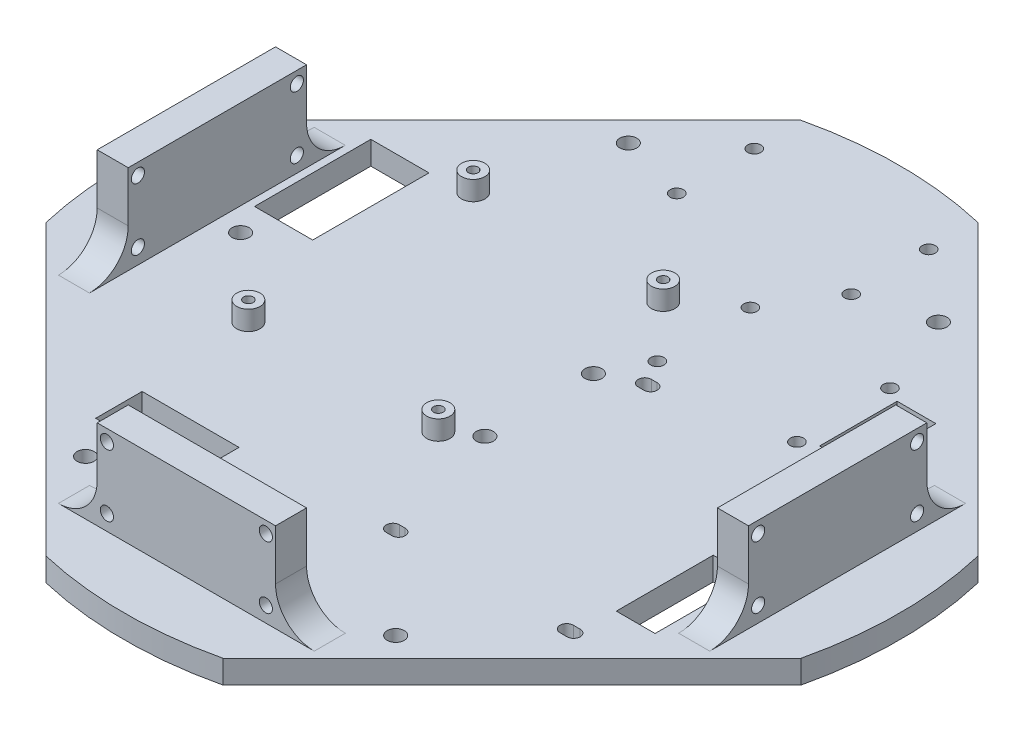
SolidWorks part; units mm, degrees
ref_plane "Front Plane" through (0, 0, 0) normal (0, 0, 1) x (1, 0, 0)
ref_plane "Top Plane" through (0, 0, 0) normal (0, 1, 0) x (1, 0, 0)
ref_plane "Right Plane" through (0, 0, 0) normal (1, 0, 0) x (0, 0, -1)
sketch "Sketch1" plane through (0, 0, 0) normal (0, 1, 0) x (1, 0, 0)
  line L2 (97.3532, -22.8549) -> (22.8549, -97.3532)
  line L3 (97.3532, 22.8549) -> (22.8549, 97.3532)
  line L4 (-22.8549, 97.3532) -> (-97.3532, 22.8549)
  line L5 (-22.8549, -97.3532) -> (-97.3532, -22.8549)
  line L6 (100, 0) -> (-100, 0) construction
  line L7 (0, 100) -> (0, -100) construction
  arc A0 (-22.8549, -97.3532) -> (22.8549, -97.3532) centre (0, 0) ccw
  arc A1 (97.3532, -22.8549) -> (97.3532, 22.8549) centre (0, 0) ccw
  arc A2 (22.8549, 97.3532) -> (-22.8549, 97.3532) centre (0, 0) ccw
  arc A4 (-97.3532, 22.8549) -> (-97.3532, -22.8549) centre (0, 0) ccw
  dimension "D2" = 200
  dimension "D1" = 170
  dimension "D3" = 170
extrude "Boss-Extrude1" add sketch "Sketch1" along normal blind 6
sketch "Sketch2" plane through (0, 6, 0) normal (0, 1, 0) x (1, 0, 0)
  line L0 (3.5, -14) -> (10.5, -14) construction
  line L1 (-52.5, 42.5) -> (3.5, 42.5) construction
  line L2 (-52.5, 42.5) -> (-52.5, -42.5) construction
  line L3 (-52.5, -42.5) -> (3.5, -42.5) construction
  line L4 (3.5, 42.5) -> (3.5, -42.5) construction
  line L5 (-52.5, 42.5) -> (3.5, -42.5) construction
  line L6 (-52.5, -42.5) -> (3.5, 42.5) construction
  line L7 (10.5, 21) -> (60.5, 21) construction
  line L8 (10.5, 21) -> (10.5, -49) construction
  line L9 (10.5, -49) -> (60.5, -49) construction
  line L10 (60.5, 21) -> (60.5, -49) construction
  line L11 (10.5, 21) -> (60.5, -49) construction
  line L12 (10.5, -49) -> (60.5, 21) construction
  line L13 (10.5, 51) -> (50.5, 51) construction
  line L14 (10.5, 51) -> (10.5, 23) construction
  line L15 (10.5, 23) -> (50.5, 23) construction
  line L16 (50.5, 51) -> (50.5, 23) construction
  line L17 (10.5, 51) -> (50.5, 23) construction
  line L18 (10.5, 23) -> (50.5, 51) construction
  line L19 (-24.5, 0) -> (24.5, 0) construction
  line L20 (15.75, 18.5) -> (17.25, 18.5) construction
  line L21 (12.5, 25) -> (48.5, 25) construction
  line L22 (12.5, 25) -> (12.5, 49) construction
  line L23 (12.5, 49) -> (48.5, 49) construction
  line L24 (48.5, 25) -> (48.5, 49) construction
  line L25 (12.5, 25) -> (48.5, 49) construction
  line L26 (12.5, 49) -> (48.5, 25) construction
  line L27 (16.5, -46.5) -> (61.5, -46.5) construction
  line L28 (16.5, -46.5) -> (16.5, 18.5) construction
  line L29 (16.5, 18.5) -> (61.5, 18.5) construction
  line L30 (61.5, -46.5) -> (61.5, 18.5) construction
  line L33 (15.75, 20.2) -> (17.25, 20.2)
  line L34 (15.75, 16.8) -> (17.25, 16.8)
  line L35 (60.6, 18.5) -> (62.4, 18.5) construction
  line L36 (60.6, 20.2) -> (62.4, 20.2)
  line L37 (60.6, 16.8) -> (62.4, 16.8)
  line L38 (15.75, -46.5) -> (17.25, -46.5) construction
  line L39 (15.75, -44.8) -> (17.25, -44.8)
  line L40 (15.75, -48.2) -> (17.25, -48.2)
  line L41 (60.6, -46.5) -> (62.4, -46.5) construction
  line L42 (60.6, -44.8) -> (62.4, -44.8)
  line L43 (60.6, -48.2) -> (62.4, -48.2)
  line L44 (-70, 0) -> (70, 0) construction
  line L45 (-49, -19) -> (0, -19) construction
  line L46 (-49, -19) -> (-49, 39) construction
  line L47 (-49, 39) -> (0, 39) construction
  line L48 (0, -19) -> (0, 39) construction
  line L49 (-49, -19) -> (0, 39) construction
  line L50 (-49, 39) -> (0, -19) construction
  line L51 (-25, 87.5) -> (25, 87.5) construction
  line L52 (-25, 87.5) -> (-25, 62.5) construction
  line L53 (-25, 62.5) -> (25, 62.5) construction
  line L54 (25, 87.5) -> (25, 62.5) construction
  line L55 (-25, 87.5) -> (25, 62.5) construction
  line L56 (-25, 62.5) -> (25, 87.5) construction
  line L57 (-22.5, 65) -> (22.5, 65) construction
  line L58 (-22.5, 65) -> (-22.5, 85) construction
  line L59 (-22.5, 85) -> (22.5, 85) construction
  line L60 (22.5, 65) -> (22.5, 85) construction
  line L61 (-22.5, 65) -> (22.5, 85) construction
  line L62 (-22.5, 85) -> (22.5, 65) construction
  line L63 (-40, -70) -> (40, -70) construction
  line L64 (-40, -70) -> (-40, 70) construction
  line L65 (-40, 70) -> (40, 70) construction
  line L66 (40, -70) -> (40, 70) construction
  line L67 (-40, -70) -> (40, 70) construction
  line L68 (-40, 70) -> (40, -70) construction
  line L69 (3.5, 37) -> (10.5, 37) construction
  line L73 (-7.9, -10.25) -> (7.9, -10.25) construction
  line L74 (-7.9, -10.25) -> (-7.9, 10.25) construction
  line L75 (-7.9, 10.25) -> (7.9, 10.25) construction
  line L76 (7.9, -10.25) -> (7.9, 10.25) construction
  line L77 (-7.9, -10.25) -> (7.9, 10.25) construction
  line L78 (-7.9, 10.25) -> (7.9, -10.25) construction
  line L79 (7, -14) -> (7, 15.9726) construction
  line L80 (-7.4775, -48.1913) -> (-7.4775, -60.1913) construction
  line L81 (-19.4775, -46.1913) -> (-5.4775, -46.1913) construction
  line L82 (-19.4775, -46.1913) -> (-19.4775, -62.1913) construction
  line L83 (-19.4775, -62.1913) -> (-5.4775, -62.1913) construction
  line L84 (-5.4775, -46.1913) -> (-5.4775, -62.1913) construction
  line L85 (-19.4775, -46.1913) -> (-5.4775, -62.1913) construction
  line L86 (-19.4775, -62.1913) -> (-5.4775, -46.1913) construction
  line L87 (-31.848, 63.9028) -> (-31.848, 51.9028) construction
  line L88 (-43.848, 65.9028) -> (-29.848, 65.9028) construction
  line L89 (-43.848, 65.9028) -> (-43.848, 49.9028) construction
  line L90 (-43.848, 49.9028) -> (-29.848, 49.9028) construction
  line L91 (-29.848, 65.9028) -> (-29.848, 49.9028) construction
  line L92 (-43.848, 65.9028) -> (-29.848, 49.9028) construction
  line L93 (-43.848, 49.9028) -> (-29.848, 65.9028) construction
  line L95 (-47.2186, -48.1913) -> (-22.2186, -48.1913)
  line L96 (-47.2186, -48.1913) -> (-47.2186, -60.1913)
  line L97 (-47.2186, -60.1913) -> (-22.2186, -60.1913)
  line L98 (-22.2186, -48.1913) -> (-22.2186, -60.1913)
  line L99 (-47.2186, -48.1913) -> (-22.2186, -60.1913) construction
  line L100 (-47.2186, -60.1913) -> (-22.2186, -48.1913) construction
  line L101 (52.3441, 47) -> (62.3441, 47)
  line L102 (52.3441, 47) -> (52.3441, 27)
  line L103 (52.3441, 27) -> (62.3441, 27)
  line L104 (62.3441, 47) -> (62.3441, 27)
  line L105 (52.3441, 47) -> (62.3441, 27) construction
  line L106 (52.3441, 27) -> (62.3441, 47) construction
  line L107 (-59.0464, 37.6307) -> (-74.0464, 37.6307)
  line L108 (-59.0464, 37.6307) -> (-59.0464, 7.6307)
  line L109 (-59.0464, 7.6307) -> (-74.0464, 7.6307)
  line L110 (-74.0464, 37.6307) -> (-74.0464, 7.6307)
  line L111 (-59.0464, 37.6307) -> (-74.0464, 7.6307) construction
  line L112 (-59.0464, 7.6307) -> (-74.0464, 37.6307) construction
  line L113 (63.0144, -36.1093) -> (73.0144, -36.1093)
  line L114 (63.0144, -36.1093) -> (63.0144, -11.1093)
  line L115 (63.0144, -11.1093) -> (73.0144, -11.1093)
  line L116 (73.0144, -36.1093) -> (73.0144, -11.1093)
  line L117 (63.0144, -36.1093) -> (73.0144, -11.1093) construction
  line L118 (63.0144, -11.1093) -> (73.0144, -36.1093) construction
  circle A0 centre (12.5, 25) radius 1.7
  circle A1 centre (48.5, 25) radius 1.7
  circle A2 centre (48.5, 49) radius 1.7
  circle A3 centre (12.5, 49) radius 1.7
  arc A8 (15.75, 20.2) -> (15.75, 16.8) centre (15.75, 18.5) ccw
  arc A9 (17.25, 16.8) -> (17.25, 20.2) centre (17.25, 18.5) ccw
  arc A10 (60.6, 20.2) -> (60.6, 16.8) centre (60.6, 18.5) ccw
  arc A11 (62.4, 16.8) -> (62.4, 20.2) centre (62.4, 18.5) ccw
  arc A12 (15.75, -44.8) -> (15.75, -48.2) centre (15.75, -46.5) ccw
  arc A13 (17.25, -48.2) -> (17.25, -44.8) centre (17.25, -46.5) ccw
  arc A14 (60.6, -44.8) -> (60.6, -48.2) centre (60.6, -46.5) ccw
  arc A15 (62.4, -48.2) -> (62.4, -44.8) centre (62.4, -46.5) ccw
  circle A16 centre (-49, 39) radius 1.25
  circle A17 centre (0, 39) radius 1.25
  circle A18 centre (-49, -19) radius 1.25
  circle A19 centre (0, -19) radius 1.25
  circle A20 centre (-22.5, 85) radius 1.7
  circle A21 centre (22.5, 85) radius 1.7
  circle A22 centre (22.5, 65) radius 1.7
  circle A23 centre (-22.5, 65) radius 1.7
  circle A24 centre (-40, -70) radius 2.2
  circle A25 centre (40, -70) radius 2.2
  circle A26 centre (40, 70) radius 2.2
  circle A27 centre (-40, 70) radius 2.2
  circle A28 centre (-70, 0) radius 2.2
  circle A29 centre (70, 0) radius 2.2
  circle A30 centre (7, -14) radius 2.2
  circle A31 centre (7, 14) radius 2.2
  point P0 (-24.5, 0)
  point P6 (30.5, 37)
  point P7 (35.5, -14)
  point P22 (30.5, 37)
  point P30 (35.5, -14)
  point P37 (16.5, 18.5)
  point P46 (61.5, 18.5)
  point P51 (16.5, -46.5)
  point P59 (61.5, -46.5)
  point P72 (0, 75)
  point P77 (0, 75)
  point P85 (0, 0)
  point P98 (0, 0)
  point P110 (-12.4775, -54.1913)
  point P118 (-7.4775, -54.1913)
  point P119 (0, 0)
  point P130 (-24.5, 10)
  point P131 (0, 0)
  point P132 (-34.7186, -54.1913)
  point P137 (57.3441, 37)
  point P142 (-66.5464, 22.6307)
  point P148 (57.9835, 36.8207)
  point P149 (68.0144, -23.6093)
  dimension "D8" = 3.4
  dimension "D9" = 3.4
  dimension "D10" = 3.4
  dimension "D11" = 3.4
  dimension "D14" = 1.7
  dimension "D15" = 1.5
  dimension "D16" = 1.7
  dimension "D17" = 1.8
  dimension "D20" = 1.7
  dimension "D21" = 1.7
  dimension "D22" = 1.7
  dimension "D26" = 2.5
  dimension "D27" = 2.5
  dimension "D28" = 2.5
  dimension "D29" = 2.5
  dimension "D33" = 3.4
  dimension "D34" = 3.4
  dimension "D35" = 3.4
  dimension "D36" = 3.4
  dimension "D40" = 4.4
  dimension "D41" = 4.4
  dimension "D42" = 4.4
  dimension "D43" = 4.4
  dimension "D46" = 4.4
  dimension "D47" = 4.4
  dimension "D25" = 4.4
  dimension "D50" = 7
  dimension "D1" = 85
  dimension "D2" = 56
  dimension "D3" = 70
  dimension "D4" = 50
  dimension "D5" = 40
  dimension "D6" = 28
  dimension "D7" = 2
  dimension "D12" = 36
  dimension "D13" = 24
  dimension "D18" = 45
  dimension "D19" = 65
  dimension "D23" = 1.8
  dimension "D24" = 1.5
  dimension "D30" = 25
  dimension "D31" = 50
  dimension "D32" = 75
  dimension "D37" = 20
  dimension "D38" = 45
  dimension "D39" = 80
  dimension "D44" = 140
  dimension "D45" = 140
  dimension "D48" = 15.8
  dimension "D49" = 20.5
  dimension "D51" = 3.5
  dimension "D52" = 28
  dimension "D53" = 16
  dimension "D54" = 14
  dimension "D57" = 12
  dimension "D58" = 2
  dimension "D59" = 16
  dimension "D60" = 14
  dimension "D63" = 12
  dimension "D64" = 2
  dimension "D65" = 58
  dimension "D66" = 49
  dimension "D67" = 3.5
  dimension "D68" = 12
  dimension "D69" = 25
  dimension "D70" = 10
  dimension "D71" = 20
  dimension "D72" = 15
  dimension "D73" = 30
  dimension "D74" = 10
  dimension "D75" = 25
  dimension "D76" = 6
extrude "Cut-Extrude1" cut sketch "Sketch2" against normal through all
sketch "Sketch3" plane through (0, 6, 0) normal (0, 1, 0) x (1, 0, 0)
  line L0 (0, -80) -> (0, 0) construction
  line L1 (-84, -23) -> (-76, -23)
  line L2 (-84, -23) -> (-84, 23)
  line L3 (-84, 23) -> (-76, 23)
  line L4 (-76, -23) -> (-76, 23)
  line L5 (-84, -23) -> (-76, 23) construction
  line L6 (-84, 23) -> (-76, -23) construction
  line L7 (-23, -84) -> (23, -84)
  line L8 (-23, -84) -> (-23, -76)
  line L9 (-23, -76) -> (23, -76)
  line L10 (23, -84) -> (23, -76)
  line L11 (-23, -84) -> (23, -76) construction
  line L12 (-23, -76) -> (23, -84) construction
  line L13 (84, 23) -> (76, -23) construction
  line L14 (84, -23) -> (76, 23) construction
  line L15 (76, -23) -> (76, 23)
  line L16 (84, 23) -> (76, 23)
  line L17 (84, -23) -> (84, 23)
  line L18 (84, -23) -> (76, -23)
  point P0 (-80, 0)
  point P5 (0, -80)
  point P17 (80, 0)
  dimension "D1" = 8
  dimension "D2" = 8
  dimension "D3" = 46
  dimension "D4" = 46
  dimension "D5" = 80
  dimension "D6" = 80
extrude "Boss-Extrude2" add sketch "Sketch3" along normal blind 23
sketch "Sketch4" plane through (-84, 0, 0) normal (-1, 0, 0) x (0, 0, 1)
  line L1 (-20.5, 10) -> (20.5, 10) construction
  line L2 (-20.5, 10) -> (-20.5, 26) construction
  line L3 (-20.5, 26) -> (20.5, 26) construction
  line L4 (20.5, 10) -> (20.5, 26) construction
  line L5 (-20.5, 10) -> (20.5, 26) construction
  line L6 (-20.5, 26) -> (20.5, 10) construction
  line L7 (0, 18) -> (0, 58.729) construction
  line L8 (-22.5, 8) -> (22.5, 8) construction
  line L9 (-23, 29) -> (23, 29) construction
  line L10 (-22.5, 8) -> (-22.5, 28) construction
  line L11 (-22.5, 28) -> (22.5, 28) construction
  line L12 (22.5, 8) -> (22.5, 28) construction
  line L13 (-22.5, 8) -> (22.5, 28) construction
  line L14 (-22.5, 28) -> (22.5, 8) construction
  circle A1 centre (-20.5, 26) radius 1.7
  circle A2 centre (20.5, 26) radius 1.7
  circle A3 centre (20.5, 10) radius 1.7
  circle A4 centre (-20.5, 10) radius 1.7
  point P0 (0, 18)
  dimension "D1" = 3.4
  dimension "D2" = 3.4
  dimension "D3" = 3.4
  dimension "D4" = 3.4
  dimension "D5" = 11
  dimension "D6" = 16
  dimension "D7" = 45
  dimension "D8" = 20
  dimension "D9" = 41
extrude "Cut-Extrude2" cut sketch "Sketch4" against normal through all
sketch "Sketch5" plane through (0, 0, 84) normal (0, 0, 1) x (1, 0, 0)
  line L0 (-20.5, 10) -> (20.5, 10) construction
  line L1 (-20.5, 10) -> (-20.5, 26) construction
  line L2 (-20.5, 26) -> (20.5, 26) construction
  line L3 (20.5, 10) -> (20.5, 26) construction
  line L4 (-20.5, 10) -> (20.5, 26) construction
  line L5 (-20.5, 26) -> (20.5, 10) construction
  line L6 (0, 18) -> (0, 58.1939) construction
  line L7 (-22.5, 8) -> (22.5, 8) construction
  line L8 (-22.5, 8) -> (-22.5, 28) construction
  line L9 (-22.5, 28) -> (22.5, 28) construction
  line L10 (22.5, 8) -> (22.5, 28) construction
  line L11 (-22.5, 8) -> (22.5, 28) construction
  line L12 (-22.5, 28) -> (22.5, 8) construction
  line L13 (-23, 29) -> (23, 29) construction
  circle A0 centre (-20.5, 26) radius 1.7
  circle A1 centre (20.5, 26) radius 1.7
  circle A2 centre (20.5, 10) radius 1.7
  circle A3 centre (-20.5, 10) radius 1.7
  point P0 (0, 18)
  dimension "D3" = 3.4
  dimension "D4" = 3.4
  dimension "D5" = 3.4
  dimension "D1" = 20
  dimension "D2" = 45
  dimension "D6" = 41
  dimension "D7" = 16
  dimension "D8" = 1
extrude "Cut-Extrude3" cut sketch "Sketch5" against normal through all
fillet "Fillet1" radius 10 6 edges at (23, 6, 80) (-23, 6, 80) (80, 6, 23) (-80, 6, 23) (-80, 6, -23) (80, 6, -23)
ref_plane "Plane1" through (-22.2186, 6, 60.1913) normal (1, 0, 0) x (0, 0, -1)
sketch "Sketch7" plane through (0, 6, 0) normal (0, 1, 0) x (1, 0, 0)
  circle A0 centre (-49, 39) radius 3
  circle A1 centre (0, 39) radius 3
  circle A2 centre (0, -19) radius 3
  circle A3 centre (-49, -19) radius 3
  circle A4 centre (-49, -19) radius 1.25 construction
  circle A5 centre (0, -19) radius 1.25 construction
  circle A6 centre (0, 39) radius 1.25 construction
  circle A7 centre (-49, 39) radius 1.25 construction
  circle A8 centre (-49, -19) radius 1.25
  circle A9 centre (0, -19) radius 1.25
  circle A10 centre (0, 39) radius 1.25
  circle A11 centre (-49, 39) radius 1.25
  dimension "D1" = 6
  dimension "D2" = 6
  dimension "D3" = 6
  dimension "D4" = 6
extrude "Boss-Extrude3" add sketch "Sketch7" along normal blind 5
